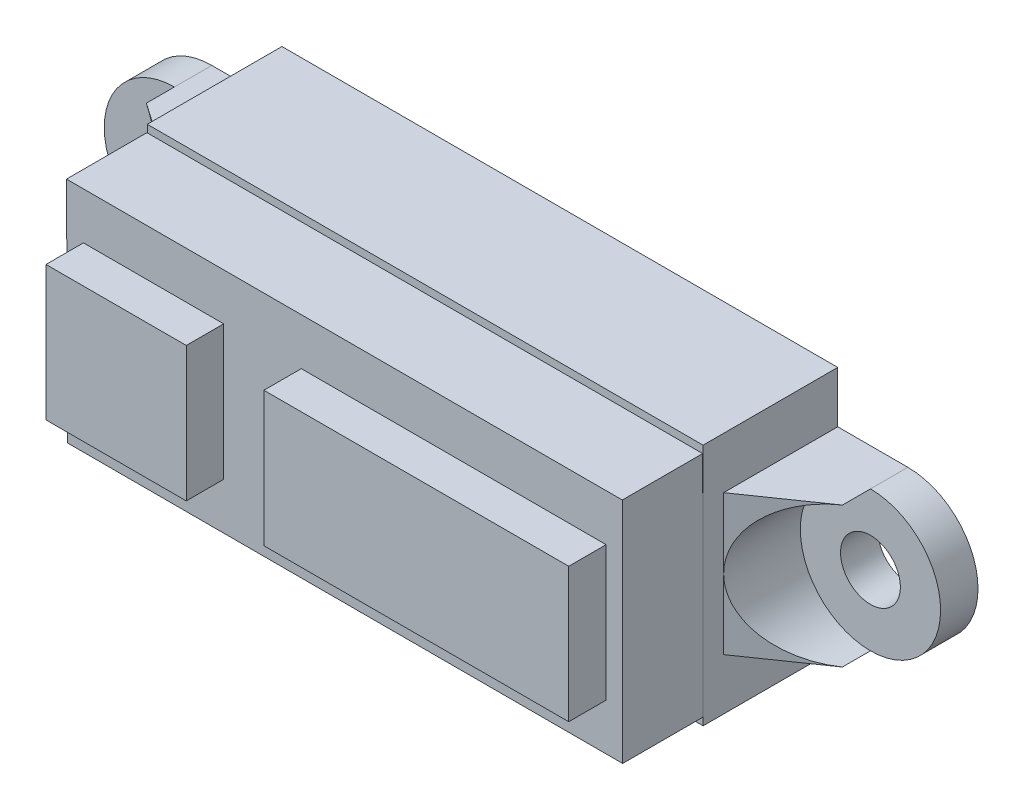
SolidWorks part; units mm, degrees
ref_plane "Front Plane" through (0, 0, 0) normal (0, 0, 1) x (1, 0, 0)
ref_plane "Top Plane" through (0, 0, 0) normal (0, 1, 0) x (1, 0, 0)
ref_plane "Right Plane" through (0, 0, 0) normal (1, 0, 0) x (0, 0, -1)
sketch "Sketch1" plane through (0, 0, 0) normal (0, 0, 1) x (1, 0, 0)
  line L1 (-14.859, 6.5) -> (14.859, 6.5)
  line L2 (-14.859, 6.5) -> (-14.859, -6.5)
  line L3 (-14.859, -6.5) -> (14.859, -6.5)
  line L4 (14.859, 6.5) -> (14.859, -6.5)
  line L5 (-14.859, 6.5) -> (14.859, -6.5) construction
  line L6 (-14.859, -6.5) -> (14.859, 6.5) construction
  point P0 (0, 0)
  dimension "D1" = 13
  dimension "D2" = 29.718
extrude "Boss-Extrude1" add sketch "Sketch1" along normal blind 7.2
sketch "Sketch2" plane through (0, 0, 7.2) normal (0, 0, 1) x (1, 0, 0)
  line L0 (14.859, -6.5) -> (14.859, 6.5) construction
  line L1 (-14.8797, 6.1002) -> (14.8383, 6.1002)
  line L2 (-14.8797, 6.1002) -> (-14.8177, -6.0917)
  line L3 (-14.8177, -6.0917) -> (14.859, -6.0917)
  line L4 (14.8383, 6.1002) -> (14.859, -6.0917)
  line L5 (-14.8797, 6.1002) -> (14.859, -6.0917) construction
  line L6 (-14.8177, -6.0917) -> (14.8383, 6.1002) construction
  point P0 (0, 0)
  dimension "D1" = 29.718
  dimension "D2" = 12.192
extrude "Boss-Extrude2" add sketch "Sketch2" along normal blind 4.3
sketch "Sketch3" plane through (0, 0, 11.5) normal (0, 0, 1) x (1, 0, 0)
  line L1 (-13.975, 3.6) -> (13.975, 3.6) construction
  line L2 (-13.975, 3.6) -> (-13.975, -3.6) construction
  line L3 (-13.975, -3.6) -> (13.975, -3.6) construction
  line L4 (13.975, 3.6) -> (13.975, -3.6) construction
  line L5 (-13.975, 3.6) -> (13.975, -3.6) construction
  line L6 (-13.975, -3.6) -> (13.975, 3.6) construction
  line L7 (-13.975, 3.6) -> (-6.475, 3.6)
  line L8 (-13.975, 3.6) -> (-13.975, -3.6)
  line L9 (-13.975, -3.6) -> (-6.475, -3.6)
  line L10 (-6.475, 3.6) -> (-6.475, -3.6)
  line L11 (13.975, 3.6) -> (-2.325, 3.6)
  line L12 (13.975, 3.6) -> (13.975, -3.6)
  line L13 (13.975, -3.6) -> (-2.325, -3.6)
  line L14 (-2.325, 3.6) -> (-2.325, -3.6)
  point P1 (0, 0)
  dimension "D1" = 7.2
  dimension "D2" = 27.95
  dimension "D3" = 7.5
  dimension "D4" = 16.3
extrude "Boss-Extrude3" add sketch "Sketch3" along normal blind 2
sketch "Sketch4" plane through (0, 0, 0) normal (0, 0, -1) x (-1, 0, 0)
  line L0 (0, 6.5) -> (0, -6.5) construction
  line L1 (-14.859, 6.5) -> (14.859, 6.5) construction
  line L2 (14.859, -6.5) -> (-14.859, -6.5) construction
  line L3 (14.859, 6.5) -> (14.859, -6.5) construction
  line L5 (-14.859, 3.75) -> (-14.859, -3.75)
  line L6 (18.609, 3.75) -> (14.859, 3.75)
  line L7 (-18.609, -3.75) -> (-14.859, -3.75)
  line L8 (18.609, -3.75) -> (14.859, -3.75)
  line L9 (14.859, 3.75) -> (14.859, -3.75)
  line L10 (-18.609, 3.75) -> (-14.859, 3.75)
  arc A0 (18.609, -3.75) -> (18.609, 3.75) centre (18.609, 0) ccw
  arc A1 (-18.609, -3.75) -> (-18.609, 3.75) centre (-18.609, 0) cw
  circle A2 centre (18.609, 0) radius 1.6
  circle A3 centre (-18.609, 0) radius 1.6
  dimension "D2" = 3.75
  dimension "D1" = 7.5
  dimension "D5" = 3.2
  dimension "D3" = 6.5
  dimension "D4" = 7.5
extrude "Boss-Extrude6" add sketch "Sketch4" against normal blind 2
sketch "Sketch6" plane through (0, 0, 0) normal (0, 0, -1) x (-1, 0, 0)
  line L0 (14.859, -6.5) -> (-14.859, -6.5) construction
  line L1 (-5.05, -6.5) -> (5.05, -6.5)
  line L2 (-5.05, -6.5) -> (-5.05, -12.5)
  line L3 (-5.05, -12.5) -> (5.05, -12.5)
  line L4 (5.05, -6.5) -> (5.05, -12.5)
  point P6 (0, -6.5)
  point P7 (0, -6.5)
  dimension "D1" = 10.1
  dimension "D2" = 6
extrude "Boss-Extrude7" add sketch "Sketch6" against normal blind 5
sketch "Sketch7" plane through (0, 0, 2) normal (0, 0, 1) x (1, 0, 0)
  line L1 (-14.859, 3.75) -> (-18.609, 3.75)
  line L2 (-14.859, 3.75) -> (-14.859, -3.75)
  line L3 (-14.859, -3.75) -> (-18.609, -3.75)
  line L4 (-18.609, 3.75) -> (-18.609, -3.75)
  line L5 (0, 6.5141) -> (0, -7.6163) construction
  line L6 (18.609, 3.75) -> (18.609, -3.75)
  line L7 (14.859, -3.75) -> (18.609, -3.75)
  line L8 (14.859, 3.75) -> (14.859, -3.75)
  line L9 (14.859, 3.75) -> (18.609, 3.75)
extrude "Boss-Extrude8" add sketch "Sketch7" along normal blind 4.1
sketch "Sketch8" plane through (0, 0, 6.1) normal (0, 0, 1) x (1, 0, 0)
  line L0 (-18.609, 0) -> (-14.859, 0) construction
  line L1 (-18.609, 3.75) -> (-18.609, -3.75) construction
  line L2 (-14.859, -3.75) -> (-14.859, 3.75) construction
  line L3 (-18.609, 3.75) -> (-18.609, -3.75) construction
  line L5 (0, 6.6491) -> (0, -6.3225) construction
  line L6 (18.609, 3.75) -> (18.609, -3.75) construction
  line L7 (18.609, 0) -> (14.859, 0) construction
  circle A0 centre (-18.609, 0) radius 3.75
  circle A1 centre (18.609, 0) radius 3.75
  dimension "D1" = 7.5
extrude "Cut-Extrude1" cut sketch "Sketch8" against normal blind 4.1
sketch "Sketch9" plane through (0, 3.75, 0) normal (0, 1, 0) x (1, 0, 0)
  line L0 (-18.609, -3.5) -> (-15.0403, -3.5) construction
  line L1 (-18.609, -6.1) -> (-18.609, -2) construction
  line L2 (-22.359, -2) -> (-18.609, -2) construction
  line L3 (-18.609, -3.5) -> (-14.859, -6.1)
  line L4 (-14.859, -6.1) -> (-18.609, -6.1)
  line L5 (-18.609, -6.1) -> (-18.609, -3.5)
  line L6 (0, 0) -> (0, -10.2338) construction
  line L7 (18.609, -6.1) -> (18.609, -3.5)
  line L8 (14.859, -6.1) -> (18.609, -6.1)
  line L9 (18.609, -3.5) -> (14.859, -6.1)
  dimension "D1" = 1.5
extrude "Cut-Extrude2" cut sketch "Sketch9" against normal through all
